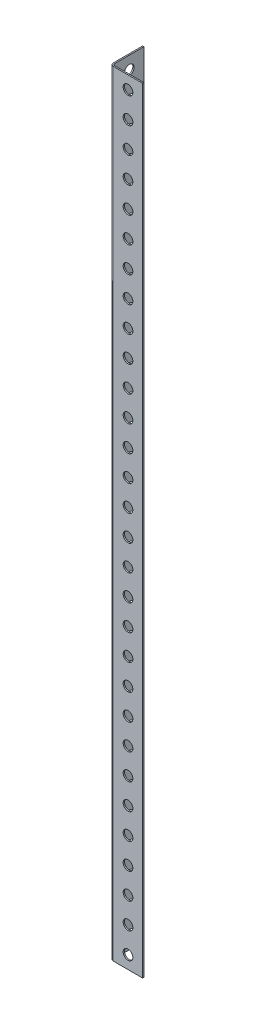
SolidWorks part; units mm, degrees
material "AISI 1020"
ref_plane "Front Plane" through (0, 0, 0) normal (0, 0, 1) x (1, 0, 0)
ref_plane "Top Plane" through (0, 0, 0) normal (0, 1, 0) x (1, 0, 0)
ref_plane "Right Plane" through (0, 0, 0) normal (1, 0, 0) x (0, 0, -1)
sketch "Sketch1" plane through (0, 0, 0) normal (0, 1, 0) x (1, 0, 0)
  line L0 (1.27, 30.48) -> (30.48, 30.48)
  line L1 (0, 0) -> (31.75, 0)
  line L2 (0, 0) -> (0, 31.75)
  line L3 (0, 31.75) -> (31.75, 31.75)
  line L4 (31.75, 0) -> (31.75, 31.75)
  line L5 (30.48, 1.27) -> (30.48, 30.48)
  line L6 (1.27, 1.27) -> (30.48, 1.27)
  line L7 (1.27, 1.27) -> (1.27, 30.48)
  line L8 (1.27, 30.48) -> (1.27, 31.75)
  line L9 (30.48, 1.27) -> (31.75, 1.27)
  dimension "D1" = 31.75
  dimension "D2" = 31.75
  dimension "D3" = 1.27
extrude "Boss-Extrude1" add sketch "Sketch1" along normal blind 1219.2 contours L9 L6 L7 L8 L3 L2 L1 L4
sketch "Sketch3" plane through (0, 0, 0) normal (-1, 0, 0) x (0, 0, 1)
  line L0 (-17.4625, 0) -> (-17.4625, 12.7) construction
  line L2 (-31.75, 1219.2) -> (-31.75, 0) construction
  circle A0 centre (-17.4625, 12.7) radius 4.7625
  circle A1 centre (-17.4625, 38.1) radius 4.7625
  circle A2 centre (-17.4625, 63.5) radius 4.7625
  circle A3 centre (-17.4625, 88.9) radius 4.7625
  circle A4 centre (-17.4625, 114.3) radius 4.7625
  circle A5 centre (-17.4625, 139.7) radius 4.7625
  circle A6 centre (-17.4625, 165.1) radius 4.7625
  circle A7 centre (-17.4625, 190.5) radius 4.7625
  circle A8 centre (-17.4625, 215.9) radius 4.7625
  circle A9 centre (-17.4625, 241.3) radius 4.7625
  circle A10 centre (-17.4625, 266.7) radius 4.7625
  circle A11 centre (-17.4625, 292.1) radius 4.7625
  circle A12 centre (-17.4625, 317.5) radius 4.7625
  circle A13 centre (-17.4625, 342.9) radius 4.7625
  circle A14 centre (-17.4625, 368.3) radius 4.7625
  circle A15 centre (-17.4625, 393.7) radius 4.7625
  circle A16 centre (-17.4625, 419.1) radius 4.7625
  circle A17 centre (-17.4625, 444.5) radius 4.7625
  circle A18 centre (-17.4625, 469.9) radius 4.7625
  circle A19 centre (-17.4625, 495.3) radius 4.7625
  circle A20 centre (-17.4625, 520.7) radius 4.7625
  circle A21 centre (-17.4625, 546.1) radius 4.7625
  circle A22 centre (-17.4625, 571.5) radius 4.7625
  circle A23 centre (-17.4625, 596.9) radius 4.7625
  circle A24 centre (-17.4625, 622.3) radius 4.7625
  circle A25 centre (-17.4625, 647.7) radius 4.7625
  circle A26 centre (-17.4625, 673.1) radius 4.7625
  circle A27 centre (-17.4625, 698.5) radius 4.7625
  circle A28 centre (-17.4625, 723.9) radius 4.7625
  circle A29 centre (-17.4625, 749.3) radius 4.7625
  circle A30 centre (-17.4625, 774.7) radius 4.7625
  circle A31 centre (-17.4625, 800.1) radius 4.7625
  circle A32 centre (-17.4625, 825.5) radius 4.7625
  circle A33 centre (-17.4625, 850.9) radius 4.7625
  circle A34 centre (-17.4625, 876.3) radius 4.7625
  circle A35 centre (-17.4625, 901.7) radius 4.7625
  circle A36 centre (-17.4625, 927.1) radius 4.7625
  circle A37 centre (-17.4625, 952.5) radius 4.7625
  circle A38 centre (-17.4625, 977.9) radius 4.7625
  circle A39 centre (-17.4625, 1003.3) radius 4.7625
  circle A40 centre (-17.4625, 1028.7) radius 4.7625
  circle A41 centre (-17.4625, 1054.1) radius 4.7625
  circle A42 centre (-17.4625, 1079.5) radius 4.7625
  circle A43 centre (-17.4625, 1104.9) radius 4.7625
  circle A44 centre (-17.4625, 1130.3) radius 4.7625
  circle A45 centre (-17.4625, 1155.7) radius 4.7625
  circle A46 centre (-17.4625, 1181.1) radius 4.7625
  circle A47 centre (-17.4625, 1206.5) radius 4.7625
  dimension "D1" = 9.525
  dimension "D2" = 12.7
  dimension "D4" = 14.2875
  dimension "D3" = 48
extrude "Cut-Extrude1" cut sketch "Sketch3" against normal up to next (1.27 mm away)
sketch "Sketch4" plane through (0, 0, 0) normal (0, 0, 1) x (1, 0, 0)
  line L0 (17.4625, 1219.2) -> (17.4625, 1206.5) construction
  line L2 (31.75, 1219.2) -> (31.75, 0) construction
  circle A0 centre (17.4625, 1206.5) radius 4.7625
  circle A1 centre (17.4625, 1181.1) radius 4.7625
  circle A2 centre (17.4625, 1155.7) radius 4.7625
  circle A3 centre (17.4625, 1130.3) radius 4.7625
  circle A4 centre (17.4625, 1104.9) radius 4.7625
  circle A5 centre (17.4625, 1079.5) radius 4.7625
  circle A6 centre (17.4625, 1054.1) radius 4.7625
  circle A7 centre (17.4625, 1028.7) radius 4.7625
  circle A8 centre (17.4625, 1003.3) radius 4.7625
  circle A9 centre (17.4625, 977.9) radius 4.7625
  circle A10 centre (17.4625, 952.5) radius 4.7625
  circle A11 centre (17.4625, 927.1) radius 4.7625
  circle A12 centre (17.4625, 901.7) radius 4.7625
  circle A13 centre (17.4625, 876.3) radius 4.7625
  circle A14 centre (17.4625, 850.9) radius 4.7625
  circle A15 centre (17.4625, 825.5) radius 4.7625
  circle A16 centre (17.4625, 800.1) radius 4.7625
  circle A17 centre (17.4625, 774.7) radius 4.7625
  circle A18 centre (17.4625, 749.3) radius 4.7625
  circle A19 centre (17.4625, 723.9) radius 4.7625
  circle A20 centre (17.4625, 698.5) radius 4.7625
  circle A21 centre (17.4625, 673.1) radius 4.7625
  circle A22 centre (17.4625, 647.7) radius 4.7625
  circle A23 centre (17.4625, 622.3) radius 4.7625
  circle A24 centre (17.4625, 596.9) radius 4.7625
  circle A25 centre (17.4625, 571.5) radius 4.7625
  circle A26 centre (17.4625, 546.1) radius 4.7625
  circle A27 centre (17.4625, 520.7) radius 4.7625
  circle A28 centre (17.4625, 495.3) radius 4.7625
  circle A29 centre (17.4625, 469.9) radius 4.7625
  circle A30 centre (17.4625, 444.5) radius 4.7625
  circle A31 centre (17.4625, 419.1) radius 4.7625
  circle A32 centre (17.4625, 393.7) radius 4.7625
  circle A33 centre (17.4625, 368.3) radius 4.7625
  circle A34 centre (17.4625, 342.9) radius 4.7625
  circle A35 centre (17.4625, 317.5) radius 4.7625
  circle A36 centre (17.4625, 292.1) radius 4.7625
  circle A37 centre (17.4625, 266.7) radius 4.7625
  circle A38 centre (17.4625, 241.3) radius 4.7625
  circle A39 centre (17.4625, 215.9) radius 4.7625
  circle A40 centre (17.4625, 190.5) radius 4.7625
  circle A41 centre (17.4625, 165.1) radius 4.7625
  circle A42 centre (17.4625, 139.7) radius 4.7625
  circle A43 centre (17.4625, 114.3) radius 4.7625
  circle A44 centre (17.4625, 88.9) radius 4.7625
  circle A45 centre (17.4625, 63.5) radius 4.7625
  circle A46 centre (17.4625, 38.1) radius 4.7625
  circle A47 centre (17.4625, 12.7) radius 4.7625
  dimension "D1" = 9.525
  dimension "D2" = 12.7
  dimension "D4" = 14.2875
  dimension "D3" = 48
extrude "Cut-Extrude2" cut sketch "Sketch4" against normal up to next (1.27 mm away)
fillet "Fillet1" radius 3.175 1 edges at (0, 609.6, 0)
fillet "Fillet2" radius 1.5875 1 edges at (1.27, 609.6, -1.27)
sketch "Sketch5" plane through (0, 1219.2, 0) normal (0, 1, 0) x (1, 0, 0)
  line L12 (0, 31.75) -> (0, 3.175)
  line L13 (3.175, 0) -> (31.75, 0)
  line L14 (31.75, 0) -> (31.75, 1.27)
  line L15 (31.75, 1.27) -> (2.8575, 1.27)
  line L16 (1.27, 2.8575) -> (1.27, 31.75)
  line L17 (1.27, 31.75) -> (0, 31.75)
  line L18 (0, 31.75) -> (0, 3.175)
  line L19 (3.175, 0) -> (31.75, 0)
  line L20 (31.75, 0) -> (31.75, 1.27)
  line L21 (31.75, 1.27) -> (2.8575, 1.27)
  line L22 (1.27, 2.8575) -> (1.27, 31.75)
  line L23 (1.27, 31.75) -> (0, 31.75)
  arc A4 (0, 3.175) -> (3.175, 0) centre (3.175, 3.175) ccw
  arc A5 (1.27, 2.8575) -> (2.8575, 1.27) centre (2.8575, 2.8575) ccw
  arc A6 (0, 3.175) -> (3.175, 0) centre (3.175, 3.175) ccw
  arc A7 (1.27, 2.8575) -> (2.8575, 1.27) centre (2.8575, 2.8575) ccw
  dimension "D1" = 0
extrude "Cut-Extrude3" cut sketch "Sketch5" against normal blind 457.2
